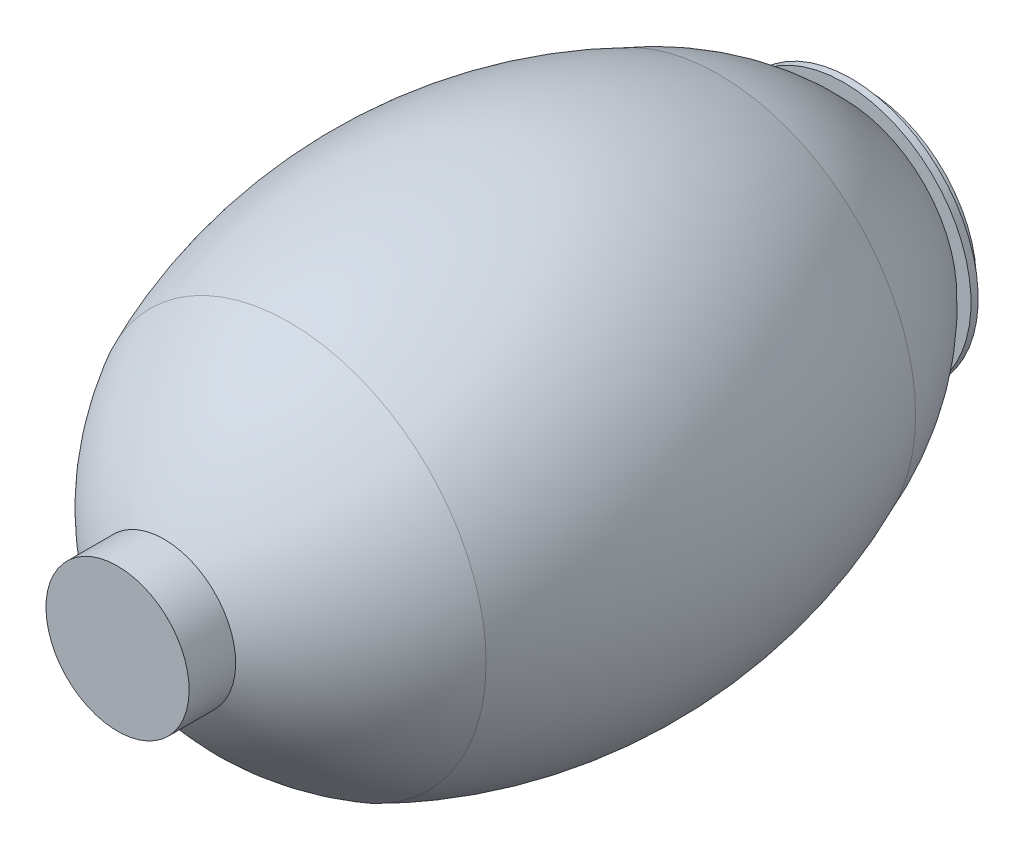
SolidWorks part; units mm, degrees
ref_plane "Front Plane" through (0, 0, 0) normal (0, 0, 1) x (1, 0, 0)
ref_plane "Top Plane" through (0, 0, 0) normal (0, 1, 0) x (1, 0, 0)
ref_plane "Right Plane" through (0, 0, 0) normal (1, 0, 0) x (0, 0, -1)
sketch "Sketch1" plane through (0, 0, 0) normal (1, 0, 0) x (0, 0, -1)
  line L0 (0, 0) -> (0, 20)
  line L1 (0, 20) -> (13, 20)
  line L2 (203, 31.5) -> (203, 35.5)
  line L3 (203, 35.5) -> (205, 35.5)
  line L4 (205, 35.5) -> (205, 31)
  line L5 (205, 31) -> (209, 31)
  line L6 (209, 31) -> (209, 0)
  line L7 (209, 0) -> (0, 0)
  line L8 (108, 67.5) -> (176.7271, 67.5) construction
  line L9 (108, 67.5) -> (108, 0) construction
  arc A0 (13, 20) -> (48, 55) centre (91.6862, -23.6862) cw
  arc A1 (48, 55) -> (168, 55) centre (108, -82.75) cw
  arc A2 (168, 55) -> (203, 31.5) centre (136.7263, -29.3917) cw
  dimension "D1" = 67.5
  dimension "D13" = 90
  dimension "D14" = 90
  dimension "D2" = 55
  dimension "D3" = 120
  dimension "D4" = 13
  dimension "D5" = 31.5
  dimension "D6" = 20
  dimension "D7" = 35
  dimension "D8" = 35
  dimension "D9" = 35.5
  dimension "D10" = 2
  dimension "D11" = 4
  dimension "D12" = 31
revolve "Revolve1" add sketch "Sketch1" angle 360 about L7
